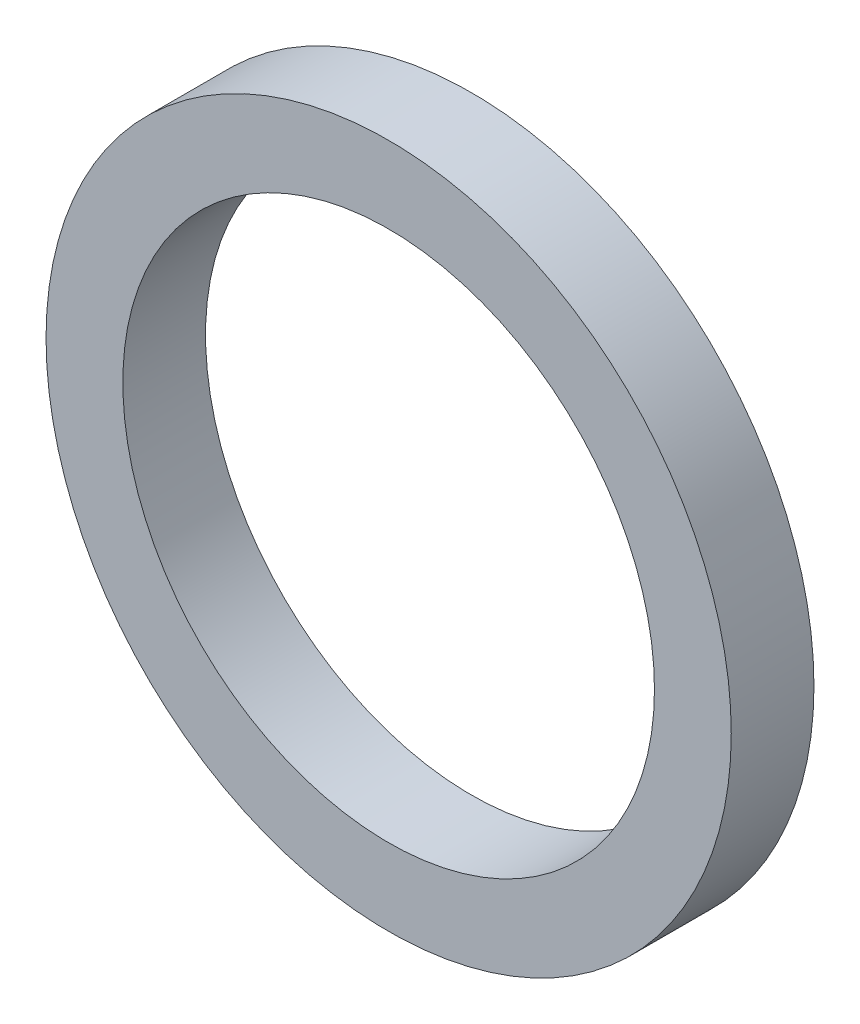
SolidWorks part; units mm, degrees
ref_plane "前视基准面" through (0, 0, 0) normal (0, 0, 1) x (1, 0, 0)
ref_plane "上视基准面" through (0, 0, 0) normal (0, 1, 0) x (1, 0, 0)
ref_plane "右视基准面" through (0, 0, 0) normal (1, 0, 0) x (0, 0, -1)
other "Configuration Table"
sketch "草图1" plane through (0, 0, 0) normal (0, 0, 1) x (1, 0, 0)
  circle A0 centre (0, 0) radius 22.5
  dimension "D1" = 45
extrude "拉伸-薄壁1" add sketch "草图1" along normal blind 7 thin
